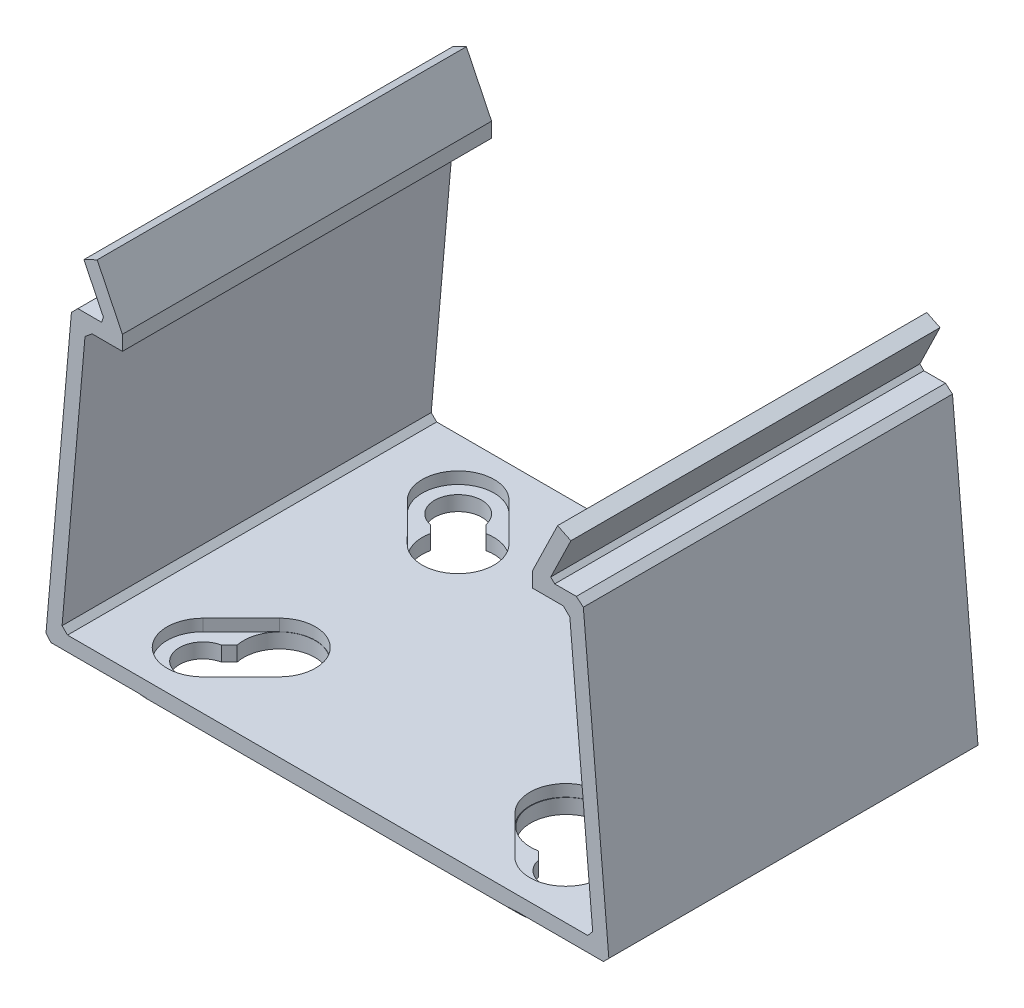
SolidWorks part; units mm, degrees
ref_plane "Front Plane" through (0, 0, 0) normal (0, 0, 1) x (1, 0, 0)
ref_plane "Top Plane" through (0, 0, 0) normal (0, 1, 0) x (1, 0, 0)
ref_plane "Right Plane" through (0, 0, 0) normal (1, 0, 0) x (0, 0, -1)
sketch "Sketch1" plane through (0, 0, 0) normal (0, 0, 1) x (1, 0, 0)
  line L0 (0, 0) -> (0, 24) construction
  line L1 (-34.5956, 39) -> (-29.9866, 39)
  line L2 (-32.7629, 37) -> (-36, 0)
  line L3 (-36, 0) -> (0, 0)
  line L4 (-34.5956, 39) -> (-38.1826, -2)
  line L5 (-38.1826, -2) -> (0, -2)
  line L6 (-32.7629, 37) -> (-27.7629, 37)
  line L7 (-27.7629, 39) -> (-27.7629, 37)
  line L8 (38.1826, -2) -> (0, -2)
  line L9 (36, 0) -> (0, 0)
  line L10 (27.7629, 39) -> (27.7629, 37)
  line L11 (32.7629, 37) -> (27.7629, 37)
  line L12 (34.5956, 39) -> (38.1826, -2)
  line L13 (32.7629, 37) -> (36, 0)
  line L14 (34.5956, 39) -> (29.9866, 39)
  line L15 (-27.7629, 39) -> (-31.1793, 46.0303)
  line L16 (-29.9866, 39) -> (-32.9781, 45.1562)
  line L17 (-31.1793, 46.0303) -> (-32.9781, 45.1562)
  line L18 (-29.5618, 38.1259) -> (-32.9781, 45.1562) construction
  line L19 (-34.5956, 39) -> (-27.7629, 39) construction
  line L20 (31.1793, 46.0303) -> (32.9781, 45.1562)
  line L21 (29.9866, 39) -> (32.9781, 45.1562)
  line L22 (27.7629, 39) -> (31.1793, 46.0303)
  dimension "D1" = 85
  dimension "D2" = 37
  dimension "D3" = 36
  dimension "D4" = 2
  dimension "D5" = 5
  dimension "D6" = 2
extrude "Boss-Extrude1" add sketch "Sketch1" along normal blind 50
sketch "Sketch5" plane through (0, -2, 0) normal (0, -1, 0) x (1, 0, 0)
  line L0 (-31.5, 0) -> (-31.5, 50)
  line L1 (-38.1826, 50) -> (38.1826, 50) construction
  line L3 (-31.5, 50) -> (31.5, 50)
  line L4 (-31.5, 0) -> (31.5, 0)
  line L5 (0, 0) -> (0, 50) construction
  line L6 (24.3, 15) -> (-24.3, 15) construction
  line L7 (31.5, 0) -> (31.5, 50)
  dimension "D1" = 48.6
  dimension "D2" = 63
extrude "Boss-Extrude2" add sketch "Sketch5" along normal blind 1.6
sketch "Sketch9" plane through (0, 0, 0) normal (0, 1, 0) x (1, 0, 0)
  line L1 (-5, -45) -> (-5, -5)
  line L2 (-5, -45) -> (5, -45)
  line L3 (5, -45) -> (5, -5)
  line L4 (-5, -5) -> (5, -5)
  line L5 (-5, -45) -> (5, -5) construction
  line L6 (5, -45) -> (-5, -5) construction
  point P0 (0, -25)
  dimension "D1" = 10
  dimension "D3" = 40
chamfer "Chamfer6" distance 0.8 angle 45 4 edges at (-38.1826, -2, 25) (38.1826, -2, 25) (36, 0, 25) (-36, 0, 25)
chamfer "Chamfer7" distance 0.8 angle 45 6 edges at (-32.7629, 37, 25) (32.7629, 37, 25) (34.5956, 39, 25) (-34.5956, 39, 25) (29.9866, 39, 25) (-29.9866, 39, 25)
fillet "Fillet1" radius 7 4 edges at (-31.5, -2.8, 50) (-31.5, -2.8, 0) (31.5, -2.8, 0) (31.5, -2.8, 50)
chamfer "Chamfer10" distance 1.5 angle 45 8 edges at (31.5, -3.6, 25) (29.4497, -3.6, 47.9497) (29.4497, -3.6, 2.0503) (0, -3.6, 50) (0, -3.6, 0) (-29.4497, -3.6, 47.9497) (-29.4497, -3.6, 2.0503) (-31.5, -3.6, 25)
sketch "Sketch15" plane through (0, 0, 0) normal (0, 1, 0) x (1, 0, 0)
  line L0 (23.9726, -41.6053) -> (18.8041, -36.4369)
  line L1 (21.475, -42.8663) -> (20.4282, -41.8195)
  line L2 (25.2336, -39.1077) -> (24.1868, -38.061)
  line L3 (-31.1793, -25) -> (31.1793, -25) construction
  line L4 (-31.1793, -50) -> (-31.1793, 0) construction
  line L5 (31.1793, -50) -> (31.1793, 0) construction
  line L6 (0.0308, -50) -> (0, 0) construction
  line L7 (35.2616, -50) -> (-35.2, -50) construction
  line L8 (-25.1854, -39.1388) -> (-24.1399, -38.0907)
  line L9 (-21.4222, -42.8927) -> (-20.3768, -41.8446)
  line L10 (-23.9213, -41.6348) -> (-18.7593, -36.46)
  line L11 (25.2336, -10.8923) -> (24.1868, -11.939)
  line L12 (21.475, -7.1337) -> (20.4282, -8.1805)
  line L13 (23.9726, -8.3947) -> (18.8041, -13.5631)
  line L14 (-23.9213, -8.3652) -> (-18.7593, -13.54)
  line L15 (-21.4222, -7.1073) -> (-20.3768, -8.1554)
  line L16 (-25.1854, -10.8612) -> (-24.1399, -11.9093)
  arc A0 (21.475, -42.8663) -> (25.2336, -39.1077) centre (24.6146, -42.2473) ccw
  arc A1 (24.1868, -38.061) -> (20.4282, -41.8195) centre (19.4462, -37.0789) ccw
  arc A2 (-24.1399, -38.0907) -> (-20.3768, -41.8446) centre (-19.4005, -37.1028) cw
  arc A3 (-21.4222, -42.8927) -> (-25.1854, -39.1388) centre (-24.5626, -42.2776) cw
  arc A4 (24.1868, -11.939) -> (20.4282, -8.1805) centre (19.4462, -12.9211) cw
  arc A5 (21.475, -7.1337) -> (25.2336, -10.8923) centre (24.6146, -7.7527) cw
  arc A6 (-21.4222, -7.1073) -> (-25.1854, -10.8612) centre (-24.5626, -7.7224) ccw
  arc A7 (-24.1399, -11.9093) -> (-20.3768, -8.1554) centre (-19.4005, -12.8972) ccw
extrude "Cut-Extrude5" cut sketch "Sketch15" against normal up to next
sketch "Sketch16" plane through (0, 0, 0) normal (0, 1, 0) x (1, 0, 0)
  line L0 (-19.4005, -37.1028) -> (-24.5626, -42.2776) construction
  line L1 (-15.9516, -40.5432) -> (-21.1137, -45.718)
  line L2 (-22.8494, -33.6624) -> (-28.0114, -38.8372)
  line L3 (-27.7629, -25) -> (27.7629, -25) construction
  line L4 (-27.7629, -50) -> (-27.7629, 0) construction
  line L5 (27.7629, -50) -> (27.7629, 0) construction
  line L6 (0, -45) -> (0, -5) construction
  line L7 (-5, -45) -> (5, -45) construction
  line L8 (5, -5) -> (-5, -5) construction
  line L9 (-19.4005, -12.8972) -> (-24.5626, -7.7224) construction
  line L10 (-15.9516, -9.4568) -> (-21.1137, -4.282)
  line L11 (-22.8494, -16.3376) -> (-28.0114, -11.1628)
  line L12 (19.4005, -37.1028) -> (24.5626, -42.2776) construction
  line L13 (15.9516, -40.5432) -> (21.1137, -45.718)
  line L14 (22.8494, -33.6624) -> (28.0114, -38.8372)
  line L15 (19.4005, -12.8972) -> (24.5626, -7.7224) construction
  line L16 (15.9516, -9.4568) -> (21.1137, -4.282)
  line L17 (22.8494, -16.3376) -> (28.0114, -11.1628)
  arc A0 (-15.9516, -40.5432) -> (-22.8494, -33.6624) centre (-19.4005, -37.1028) ccw
  arc A1 (-28.0114, -38.8372) -> (-21.1137, -45.718) centre (-24.5626, -42.2776) ccw
  arc A2 (-15.9516, -9.4568) -> (-22.8494, -16.3376) centre (-19.4005, -12.8972) cw
  arc A3 (-28.0114, -11.1628) -> (-21.1137, -4.282) centre (-24.5626, -7.7224) cw
  arc A4 (15.9516, -40.5432) -> (22.8494, -33.6624) centre (19.4005, -37.1028) cw
  arc A5 (28.0114, -38.8372) -> (21.1137, -45.718) centre (24.5626, -42.2776) cw
  arc A6 (15.9516, -9.4568) -> (22.8494, -16.3376) centre (19.4005, -12.8972) ccw
  arc A7 (28.0114, -11.1628) -> (21.1137, -4.282) centre (24.5626, -7.7224) ccw
  point P3 (-21.9815, -39.6902)
  point P23 (-21.9815, -10.3098)
  point P30 (21.9815, -39.6902)
  point P37 (21.9815, -10.3098)
extrude "Cut-Extrude6" cut sketch "Sketch16" against normal offset from surface (1.6 mm away) 2 up to face at (22.1405, -3.6, 39.7732)
